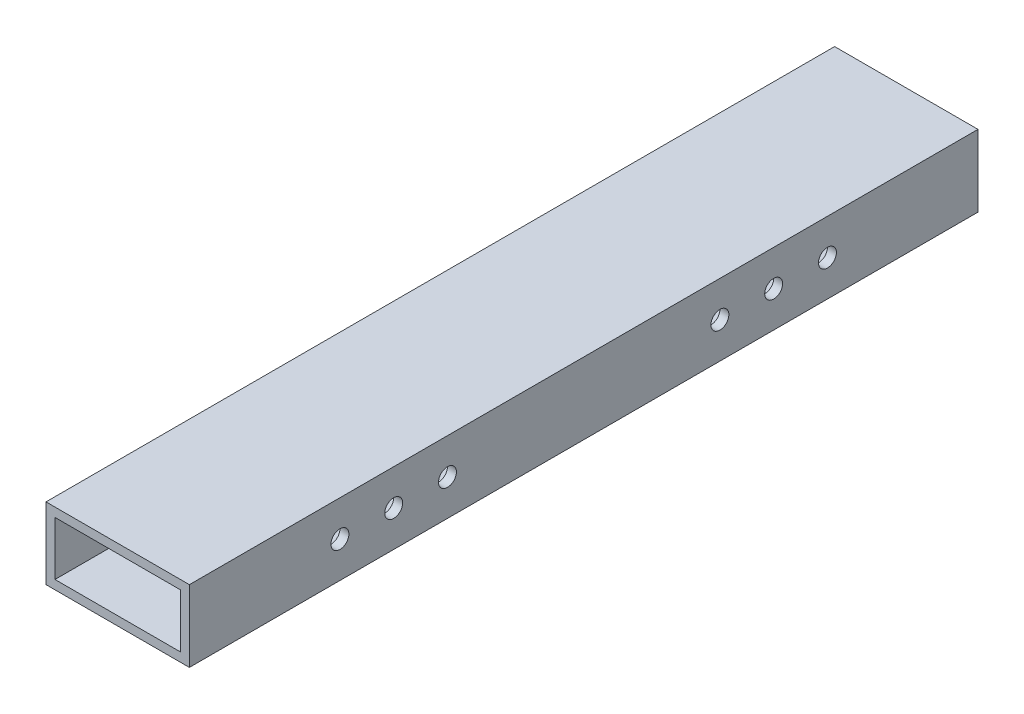
SolidWorks part; units mm, degrees
ref_plane "Front Plane" through (0, 0, 0) normal (0, 0, 1) x (1, 0, 0)
ref_plane "Top Plane" through (0, 0, 0) normal (0, 1, 0) x (1, 0, 0)
ref_plane "Right Plane" through (0, 0, 0) normal (1, 0, 0) x (0, 0, -1)
sketch "Sketch1" plane through (0, 0, 0) normal (0, 0, 1) x (1, 0, 0)
  line L0 (3.175, 22.225) -> (47.625, 22.225)
  line L1 (0, 0) -> (50.8, 0)
  line L2 (0, 0) -> (0, 25.4)
  line L3 (0, 25.4) -> (50.8, 25.4)
  line L4 (50.8, 0) -> (50.8, 25.4)
  line L5 (47.625, 3.175) -> (47.625, 22.225)
  line L6 (3.175, 3.175) -> (47.625, 3.175)
  line L7 (3.175, 3.175) -> (3.175, 22.225)
  dimension "D1" = 25.4
  dimension "D2" = 50.8
  dimension "D3" = 3.175
extrude "Boss-Extrude1" add sketch "Sketch1" along normal blind 279.4
sketch "Sketch2" plane through (50.8, 0, 0) normal (1, 0, 0) x (0, 0, -1)
  line L0 (-279.4, 0) -> (-279.4, 25.4) construction
  line L1 (-139.7, 25.4) -> (-139.7, 0) construction
  line L2 (-279.4, 25.4) -> (0, 25.4) construction
  line L3 (-279.4, 0) -> (0, 0) construction
  circle A0 centre (-226.06, 12.7) radius 3.175
  circle A1 centre (-187.96, 12.7) radius 3.175
  circle A2 centre (-207.01, 12.7) radius 3.175
  circle A3 centre (-91.44, 12.7) radius 3.175
  circle A4 centre (-53.34, 12.7) radius 3.175
  circle A5 centre (-72.39, 12.7) radius 3.175
  dimension "D7" = 6.35
  dimension "D8" = 6.35
  dimension "D9" = 6.35
  dimension "D1" = 53.34
  dimension "D2" = 19.05
  dimension "D3" = 19.05
  dimension "D4" = 12.7
  dimension "D5" = 12.7
  dimension "D6" = 12.7
extrude "Cut-Extrude1" cut sketch "Sketch2" against normal through all
